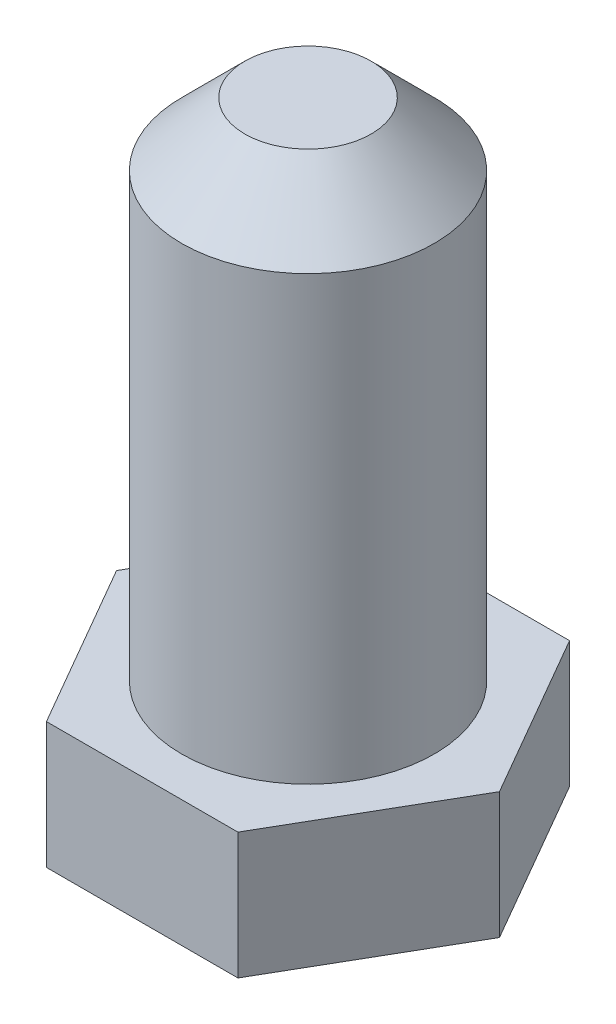
SolidWorks part; units mm, degrees
ref_plane "Front Plane" through (0, 0, 0) normal (0, 0, 1) x (1, 0, 0)
ref_plane "Top Plane" through (0, 0, 0) normal (0, 1, 0) x (1, 0, 0)
ref_plane "Right Plane" through (0, 0, 0) normal (1, 0, 0) x (0, 0, -1)
sketch "Sketch1" plane through (0, 0, 0) normal (0, 1, 0) x (1, 0, 0)
  line L1 (19.2474, 0) -> (9.6237, 16.6688)
  line L2 (9.6237, 16.6688) -> (-9.6237, 16.6687)
  line L3 (-9.6237, 16.6687) -> (-19.2474, 0)
  line L4 (-19.2474, 0) -> (-9.6237, -16.6688)
  line L5 (-9.6237, -16.6688) -> (9.6237, -16.6687)
  line L6 (9.6237, -16.6687) -> (19.2474, 0)
  circle A0 centre (0, 0) radius 16.6688 construction
  dimension "D1" = 33.3375
extrude "Boss-Extrude1" add sketch "Sketch1" along normal blind 12.7
sketch "Sketch2" plane through (0, 12.7, 0) normal (0, 1, 0) x (1, 0, 0)
  circle A0 centre (0, 0) radius 12.7
extrude "Boss-Extrude2" add sketch "Sketch2" along normal blind 44.45
sketch "Sketch3" plane through (0, 57.15, 0) normal (0, 1, 0) x (1, 0, 0)
  circle A0 centre (0, 0) radius 12.7
extrude "Boss-Extrude3" add sketch "Sketch3" along normal blind 6.35
chamfer "Chamfer1" distance 6.35 angle 45 1 edges at (0, 63.5, 12.7)
